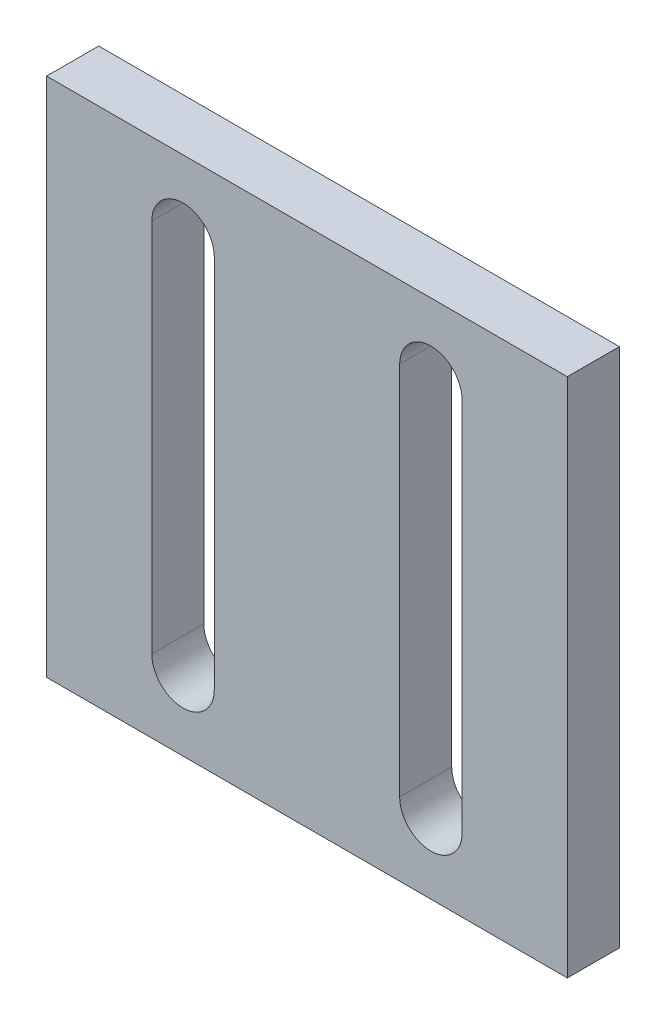
SolidWorks part; units mm, degrees
material "6061-T6 (SS)"
ref_plane "Front Plane" through (0, 0, 0) normal (0, 0, 1) x (1, 0, 0)
ref_plane "Top Plane" through (0, 0, 0) normal (0, 1, 0) x (1, 0, 0)
ref_plane "Right Plane" through (0, 0, 0) normal (1, 0, 0) x (0, 0, -1)
sketch "Sketch1" plane through (0, 0, 0) normal (0, 0, 1) x (1, 0, 0)
  line L0 (0, 0) -> (50, 0)
  line L1 (0, 0) -> (0, 50)
  line L2 (0, 50) -> (50, 50)
  line L3 (50, 50) -> (50, 0)
extrude "Boss-Extrude1" add sketch "Sketch1" along normal blind 5
sketch "Sketch2" plane through (0, 0, 5) normal (0, 0, 1) x (1, 0, 0)
  line L10 (10.1, 43) -> (10.1, 7)
  line L11 (16.1, 43) -> (16.1, 7)
  line L13 (33.9, 43) -> (33.9, 7)
  line L14 (39.9, 43) -> (39.9, 7)
  arc A0 (16.1, 7) -> (10.1, 7) centre (13.1, 7) cw
  arc A1 (16.1, 43) -> (10.1, 43) centre (13.1, 43) ccw
  arc A2 (39.9, 43) -> (33.9, 43) centre (36.9, 43) ccw
  arc A3 (39.9, 7) -> (33.9, 7) centre (36.9, 7) cw
extrude "Cut-Extrude1" cut sketch "Sketch2" against normal through all
